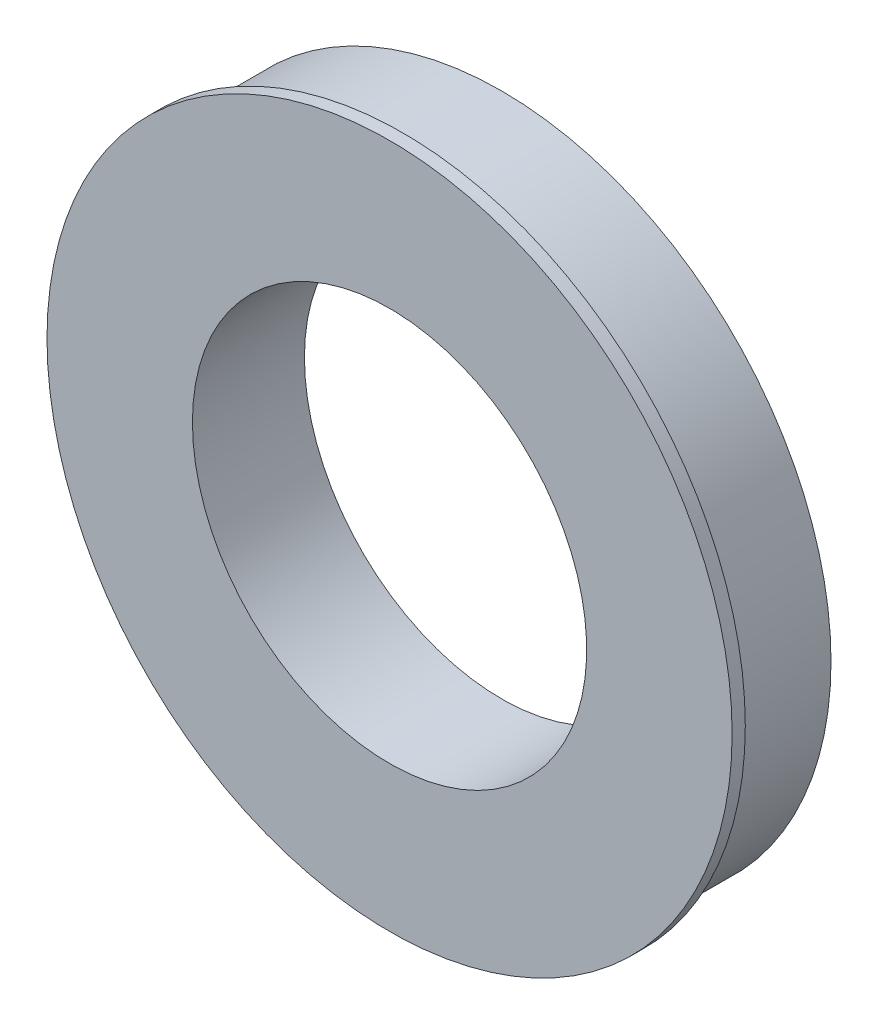
SolidWorks part; units mm, degrees
ref_plane "Front Plane" through (0, 0, 0) normal (0, 0, 1) x (1, 0, 0)
ref_plane "Top Plane" through (0, 0, 0) normal (0, 1, 0) x (1, 0, 0)
ref_plane "Right Plane" through (0, 0, 0) normal (1, 0, 0) x (0, 0, -1)
sketch "Sketch1" plane through (0, 0, 0) normal (0, 0, 1) x (1, 0, 0)
  circle A0 centre (0, 0) radius 63.5
  circle A1 centre (0, 0) radius 38
  dimension "D1" = 127
  dimension "D2" = 76
extrude "Boss-Extrude1" add sketch "Sketch1" along normal blind 19.05
sketch "Sketch3" plane through (0, 0, 19.05) normal (0, 0, 1) x (1, 0, 0)
  circle A0 centre (0, 0) radius 66.03
  circle A1 centre (0, 0) radius 38 construction
  circle A2 centre (0, 0) radius 38
  dimension "D1" = 132.06
extrude "Boss-Extrude2" add sketch "Sketch3" along normal blind 2.54
